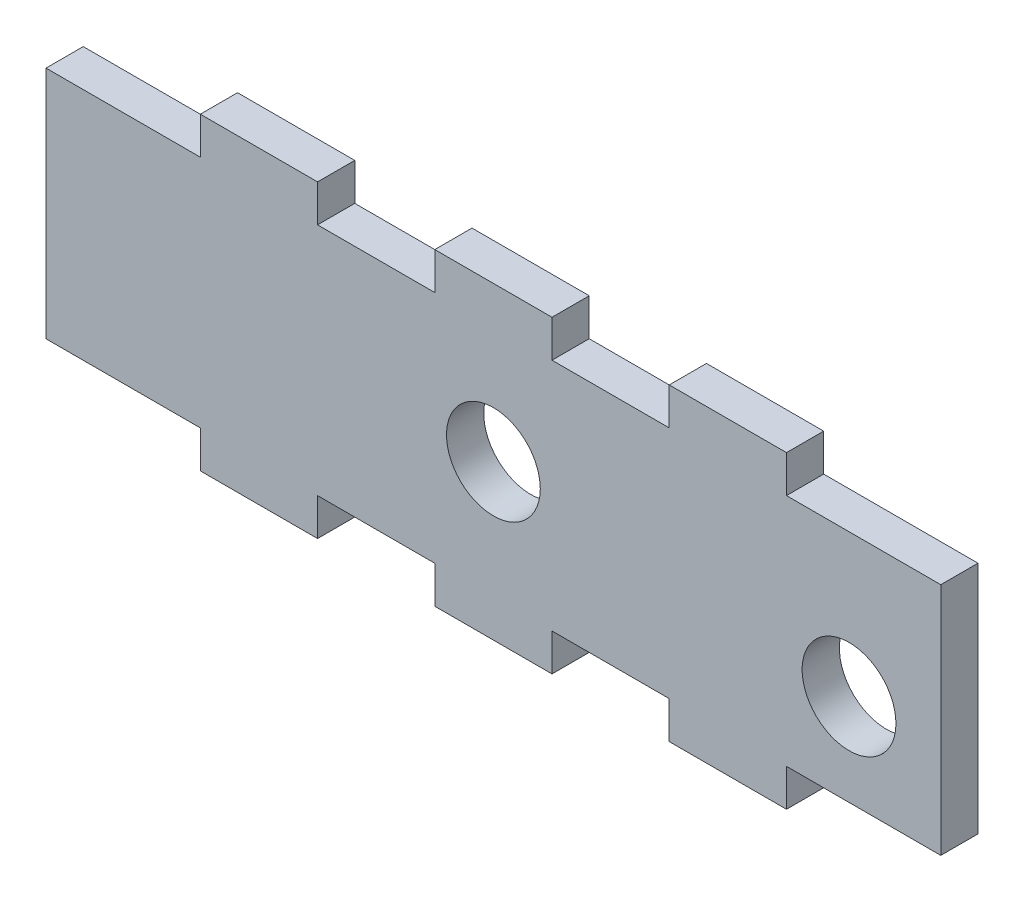
SolidWorks part; units mm, degrees
ref_plane "Plan de face" through (0, 0, 0) normal (0, 0, 1) x (1, 0, 0)
ref_plane "Plan de dessus" through (0, 0, 0) normal (0, 1, 0) x (1, 0, 0)
ref_plane "Plan de droite" through (0, 0, 0) normal (1, 0, 0) x (0, 0, -1)
sketch "Esquisse1" plane through (0, 0, 0) normal (0, 0, 1) x (1, 0, 0)
  line L1 (-82.675, 26.35) -> (82.675, 26.35)
  line L2 (-82.675, 26.35) -> (-82.675, -26.35)
  line L3 (-82.675, -26.35) -> (82.675, -26.35)
  line L4 (82.675, 26.35) -> (82.675, -26.35)
  point P4 (0, -26.35)
  point P6 (82.675, 0)
  dimension "D1" = 165.35
  dimension "D2" = 52.7
extrude "Boss.-Extru.1" add sketch "Esquisse1" along normal blind 6.35
sketch "Esquisse4" plane through (0, 0, 6.35) normal (0, 0, 1) x (1, 0, 0)
  line L0 (-82.675, -26.35) -> (82.675, -26.35) construction
  line L1 (-50, -26.35) -> (-30, -26.35)
  line L2 (-50, -26.35) -> (-50, -20)
  line L3 (-50, -20) -> (-30, -20)
  line L4 (-30, -26.35) -> (-30, -20)
  line L6 (-10, -26.35) -> (10, -26.35)
  line L7 (-10, -26.35) -> (-10, -20)
  line L8 (-10, -20) -> (10, -20)
  line L9 (10, -26.35) -> (10, -20)
  line L10 (30, -26.35) -> (50, -26.35)
  line L11 (30, -26.35) -> (30, -20)
  line L12 (30, -20) -> (50, -20)
  line L13 (50, -26.35) -> (50, -20)
  point P14 (0, -20)
  dimension "D1" = 6.35
  dimension "D2" = 20
  dimension "D3" = 20
  dimension "D4" = 20
sketch "Esquisse5" plane through (0, 0, 6.35) normal (0, 0, 1) x (1, 0, 0)
  line L1 (-30, -26.35) -> (-10, -26.35)
  line L2 (-30, -26.35) -> (-30, -20)
  line L3 (-30, -20) -> (-10, -20)
  line L4 (-10, -26.35) -> (-10, -20)
  line L5 (10, -26.35) -> (30, -26.35)
  line L6 (10, -26.35) -> (10, -20)
  line L7 (10, -20) -> (30, -20)
  line L8 (30, -26.35) -> (30, -20)
  line L9 (50, -26.35) -> (76.325, -26.35)
  line L10 (50, -26.35) -> (50, -20)
  line L11 (50, -20) -> (76.325, -20)
  line L12 (76.325, -26.35) -> (76.325, -20)
  line L14 (-50, -26.35) -> (-76.325, -26.35)
  line L15 (-50, -26.35) -> (-50, -20)
  line L16 (-50, -20) -> (-76.325, -20)
  line L17 (-76.325, -26.35) -> (-76.325, -20)
  line L18 (-50, -20) -> (-30, -20) construction
  line L19 (30, -20) -> (50, -20) construction
  line L21 (82.675, -26.35) -> (82.675, 26.35) construction
  line L23 (-82.675, 26.35) -> (-82.675, -26.35) construction
  dimension "D1" = 6.35
  dimension "D2" = 6.35
extrude "Enlèv. mat.-Extru.2" cut sketch "Esquisse5" against normal through all
mirror "Symétrie2" about plane through (0, 0, 0) normal (0, 1, 0) of "Enlèv. mat.-Extru.2"
sketch "Esquisse7" plane through (0, 0, 6.35) normal (0, 0, 1) x (1, 0, 0)
  line L1 (-82.675, 26.35) -> (-76.325, 26.35)
  line L2 (-82.675, 26.35) -> (-82.675, -26.35)
  line L3 (-82.675, -26.35) -> (-76.325, -26.35)
  line L4 (-76.325, 26.35) -> (-76.325, -26.35)
  line L5 (76.325, -26.35) -> (82.675, -26.35)
  line L6 (76.325, -26.35) -> (76.325, 26.35)
  line L7 (76.325, 26.35) -> (82.675, 26.35)
  line L8 (82.675, -26.35) -> (82.675, 26.35)
  line L9 (-76.325, -20) -> (-76.325, -26.35) construction
  line L10 (82.675, -26.35) -> (82.675, 26.35) construction
  line L11 (82.675, 26.35) -> (76.325, 26.35) construction
  line L12 (-50, -26.35) -> (-30, -26.35) construction
extrude "Enlèv. mat.-Extru.4" cut sketch "Esquisse7" against normal through all
sketch "Esquisse6" plane through (0, 0, 6.35) normal (0, 0, 1) x (1, 0, 0)
  line L1 (30, -26.35) -> (50, -26.35) construction
  line L2 (76.325, 20) -> (76.325, -20) construction
  circle A0 centre (0, 0) radius 8
  circle A1 centre (60.675, -4.35) radius 8
  dimension "D1" = 16
  dimension "D2" = 16
  dimension "D3" = 15.65
  dimension "D4" = 22
extrude "Enlèv. mat.-Extru.3" cut sketch "Esquisse6" against normal through all
